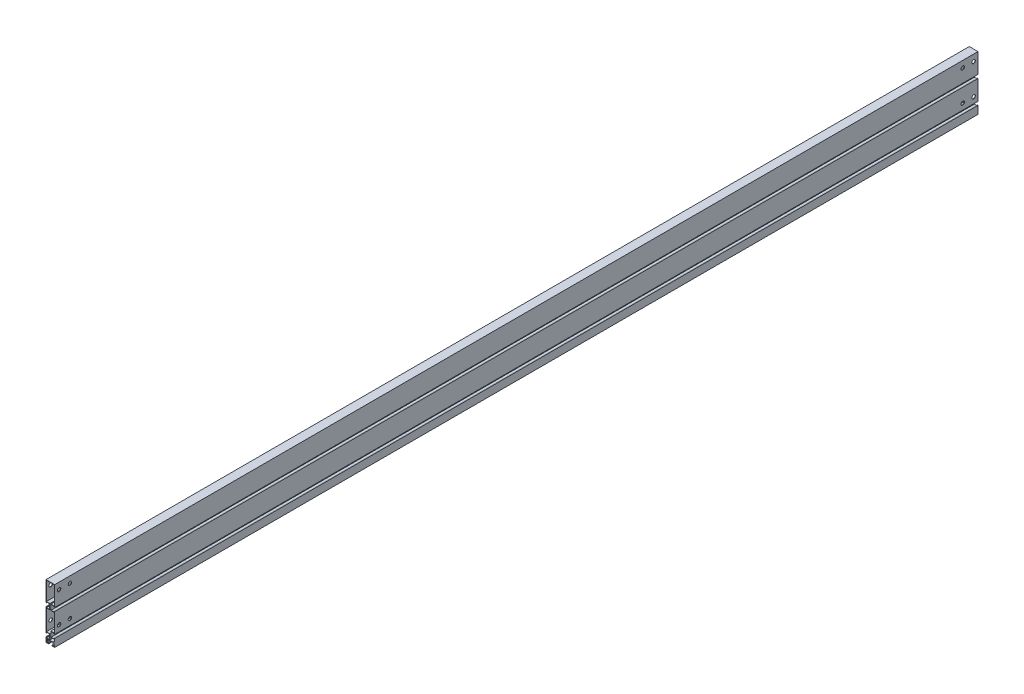
SolidWorks part; units mm, degrees
ref_plane "Ön Düzlem" through (0, 0, 0) normal (0, 0, 1) x (1, 0, 0)
ref_plane "Üst Düzlem" through (0, 0, 0) normal (0, 1, 0) x (1, 0, 0)
ref_plane "Sağ Düzlem" through (0, 0, 0) normal (1, 0, 0) x (0, 0, -1)
sketch "Sketch1" plane through (0, 0, 0) normal (0, 0, 1) x (1, 0, 0)
  line L0 (-10, -43) -> (-10, 9)
  line L1 (-10, 9) -> (-8.5, 9)
  line L2 (-8.5, 9) -> (-8.5, 7.5)
  line L3 (-8.5, 7.5) -> (-2, 7.5)
  line L4 (-2, 7.5) -> (-2, 18.5)
  line L5 (-2, 18.5) -> (-8.5, 18.5)
  line L6 (-8.5, 18.5) -> (-8.5, 17)
  line L7 (-8.5, 17) -> (-10, 17)
  line L8 (-10, 17) -> (-10, 62.5)
  line L9 (-10, 62.5) -> (10, 62.5)
  line L10 (10, 62.5) -> (10, 17)
  line L11 (10, 17) -> (8.5, 17)
  line L12 (8.5, 17) -> (8.5, 18.5)
  line L13 (8.5, 18.5) -> (2, 18.5)
  line L14 (2, 18.5) -> (2, 7.5)
  line L15 (2, 7.5) -> (8.5, 7.5)
  line L16 (8.5, 7.5) -> (8.5, 9)
  line L17 (8.5, 9) -> (10, 9)
  line L18 (10, 9) -> (10, -36.5)
  line L19 (10, -36.5) -> (8.5, -36.5)
  line L20 (8.5, -36.5) -> (8.5, -35)
  line L21 (8.5, -35) -> (2, -35)
  line L22 (2, -35) -> (2, -46)
  line L23 (2, -46) -> (8.5, -46)
  line L24 (8.5, -46) -> (8.5, -44.5)
  line L25 (8.5, -44.5) -> (10, -44.5)
  line L26 (10, -44.5) -> (10, -62.5)
  line L27 (10, -62.5) -> (4, -62.5)
  line L28 (-10, -62.5) -> (-10, -51)
  line L29 (-10, -51) -> (-8.5, -51)
  line L30 (-8.5, -51) -> (-8.5, -52.5)
  line L31 (-8.5, -52.5) -> (-2, -52.5)
  line L32 (-2, -52.5) -> (-2, -41.5)
  line L33 (-2, -41.5) -> (-8.5, -41.5)
  line L34 (-8.5, -41.5) -> (-8.5, -43)
  line L35 (-8.5, -43) -> (-10, -43)
  line L36 (0, 0) -> (0, 62.5) construction
  line L37 (0, -62.5) -> (0, 62.5) construction
  line L38 (0, 0) -> (-10, 0) construction
  line L39 (-4, -62.5) -> (-4, -61)
  line L40 (-4, -61) -> (-5.5, -61)
  line L41 (-5.5, -61) -> (-5.5, -54.5)
  line L42 (-5.5, -54.5) -> (5.5, -54.5)
  line L43 (5.5, -54.5) -> (5.5, -61)
  line L44 (5.5, -61) -> (4, -61)
  line L45 (4, -61) -> (4, -62.5)
  line L46 (-4, -62.5) -> (-10, -62.5)
  line L47 (-4, -62.5) -> (4, -62.5) construction
  line L48 (-9.2, 19.3) -> (-9.2, 61.7)
  line L49 (-9.2, 61.7) -> (9.2, 61.7)
  line L50 (9.2, 61.7) -> (9.2, 19.3)
  line L51 (9.2, 19.3) -> (9.2, 19.3)
  line L52 (9.2, 19.3) -> (9.2, 19.3)
  line L53 (9.2, 19.3) -> (1.2, 19.3)
  line L54 (1.2, 19.3) -> (1.2, 6.7)
  line L55 (1.2, 6.7) -> (9.2, 6.7)
  line L56 (9.2, 6.7) -> (9.2, 6.7)
  line L57 (9.2, 6.7) -> (9.2, 6.7)
  line L58 (9.2, 6.7) -> (9.2, -34.2)
  line L59 (9.2, -34.2) -> (9.2, -34.2)
  line L60 (9.2, -34.2) -> (9.2, -34.2)
  line L61 (9.2, -34.2) -> (1.2, -34.2)
  line L62 (1.2, -34.2) -> (1.2, -46.8)
  line L63 (1.2, -46.8) -> (9.2, -46.8)
  line L64 (9.2, -46.8) -> (9.2, -46.8)
  line L65 (9.2, -46.8) -> (9.2, -46.8)
  line L66 (9.2, -46.8) -> (9.2, -61.7)
  line L67 (9.2, -61.7) -> (6.3, -61.7)
  line L68 (6.3, -61.7) -> (6.3, -61.7)
  line L69 (6.3, -61.7) -> (6.3, -61.7)
  line L70 (6.3, -53.7) -> (6.3, -61.7)
  line L71 (-6.3, -53.7) -> (6.3, -53.7)
  line L72 (-6.3, -61.7) -> (-6.3, -53.7)
  line L73 (-6.3, -61.7) -> (-6.3, -61.7)
  line L74 (-6.3, -61.7) -> (-6.3, -61.7)
  line L75 (-6.3, -61.7) -> (-9.2, -61.7)
  line L76 (-9.2, -61.7) -> (-9.2, -53.3)
  line L77 (-9.2, -53.3) -> (-9.2, -53.3)
  line L78 (-9.2, -53.3) -> (-9.2, -53.3)
  line L79 (-9.2, -53.3) -> (-1.2, -53.3)
  line L80 (-1.2, -53.3) -> (-1.2, -40.7)
  line L81 (-1.2, -40.7) -> (-9.2, -40.7)
  line L82 (-9.2, -40.7) -> (-9.2, -40.7)
  line L83 (-9.2, -40.7) -> (-9.2, -40.7)
  line L84 (-9.2, -40.7) -> (-9.2, 6.7)
  line L85 (-9.2, 6.7) -> (-9.2, 6.7)
  line L86 (-9.2, 6.7) -> (-9.2, 6.7)
  line L87 (-9.2, 6.7) -> (-1.2, 6.7)
  line L88 (-1.2, 6.7) -> (-1.2, 19.3)
  line L89 (-1.2, 19.3) -> (-9.2, 19.3)
  line L90 (-9.2, 19.3) -> (-9.2, 19.3)
  line L91 (-9.2, 19.3) -> (-9.2, 19.3)
  dimension "D1" = 1.5
  dimension "D2" = 8
  dimension "D3" = 20
  dimension "D4" = 8
  dimension "D5" = 8
  dimension "D6" = 18
  dimension "D7" = 8
  dimension "D8" = 125
  dimension "D9" = 8
  dimension "D10" = 11
  dimension "D11" = 10
  dimension "D12" = 70
  dimension "D13" = 8
  dimension "D14" = 8
  dimension "D15" = 8
  dimension "D16" = 8
  dimension "D17" = 11
  dimension "D18" = 8
  dimension "D19" = 0.8
extrude "Boss-Extrude1" add sketch "Sketch1" along normal mid plane 2120
sketch "Sketch2" plane through (-10, 0, 0) normal (-1, 0, 0) x (0, 0, 1)
  line L0 (990.4815, 62.5) -> (990.4815, -62.5) construction
  line L1 (1060, 62.5) -> (-1060, 62.5) construction
  line L2 (1060, -62.5) -> (-1060, -62.5) construction
  line L3 (990.4815, 47.5) -> (1060, 47.5) construction
  line L5 (1060, 62.5) -> (1060, 17) construction
  line L6 (990.4815, -22.5) -> (1060, -22.5) construction
  line L7 (1060, 9) -> (1060, -43) construction
  circle A0 centre (1025, 47.5) radius 4
  circle A1 centre (1050, 47.5) radius 4
  circle A2 centre (1025, -22.5) radius 4
  circle A3 centre (1050, -22.5) radius 4
  dimension "D1" = 8
  dimension "D2" = 15
  dimension "D3" = 40
  dimension "D4" = 25
  dimension "D5" = 10
extrude "Cut-Extrude1" cut sketch "Sketch2" against normal up to surface (20 mm away) up to face at (10, 39.75, 0)
mirror "Mirror1" about plane through (0, 0, 0) normal (0, 0, 1) of "Cut-Extrude1"
sketch "Sketch4" plane through (0, -54.5, 0) normal (0, -1, 0) x (1, 0, 0)
  line L0 (0, -1060) -> (0, 1060) construction
  line L1 (-5.5, -1060) -> (5.5, -1060) construction
  line L2 (-5.5, 1060) -> (5.5, 1060) construction
sketch "Sketch5" plane through (-10, 0, 0) normal (-1, 0, 0) x (0, 0, 1)
  line L0 (-1060, -47) -> (1060, -47) construction
  line L1 (-1060, -41.5) -> (-1060, -52.5) construction
  line L2 (1060, -41.5) -> (1060, -52.5) construction
ref_plane "Plane2" through (0, -47, 0) normal (0, -1, 0) x (-1, 0, 0)
ref_plane "Plane3" through (0, 0, 0) normal (1, 0, 0) x (0, 0, -1)
sketch "Sketch6" plane through (2, 0, 0) normal (1, 0, 0) x (0, 0, -1)
  line L0 (-1060, -40.5) -> (1060, -40.5) construction
  line L1 (-1060, -46) -> (-1060, -35) construction
  line L2 (1060, -46) -> (1060, -35) construction
ref_plane "Plane4" through (0, -40.5, 0) normal (0, -1, 0) x (-1, 0, 0)
